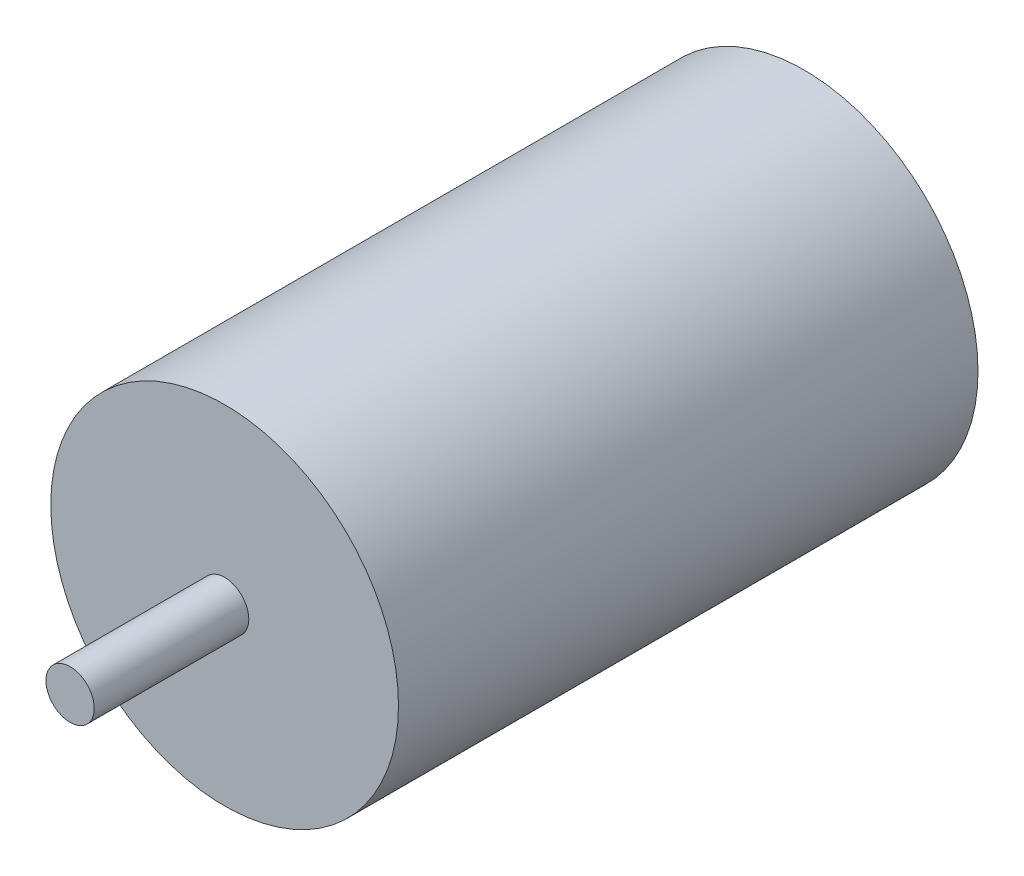
SolidWorks part; units mm, degrees
ref_plane "Front Plane" through (0, 0, 0) normal (0, 0, 1) x (1, 0, 0)
ref_plane "Top Plane" through (0, 0, 0) normal (0, 1, 0) x (1, 0, 0)
ref_plane "Right Plane" through (0, 0, 0) normal (1, 0, 0) x (0, 0, -1)
sketch "Sketch1" plane through (0, 0, 0) normal (0, 0, 1) x (1, 0, 0)
  circle A0 centre (0, 0) radius 18
  dimension "D1" = 36
extrude "Boss-Extrude1" add sketch "Sketch1" along normal blind 60
sketch "Sketch2" plane through (0, 0, 60) normal (0, 0, 1) x (1, 0, 0)
  circle A0 centre (0, 0) radius 2.5
  dimension "D1" = 5
extrude "Boss-Extrude2" add sketch "Sketch2" along normal blind 16
